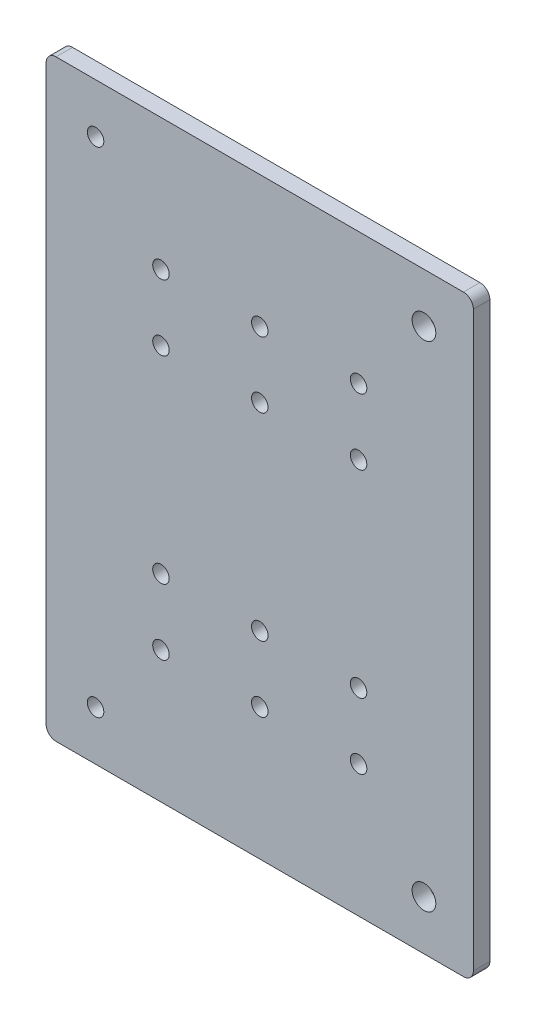
SolidWorks part; units mm, degrees
ref_plane "Płaszczyzna przednia" through (0, 0, 0) normal (0, 0, 1) x (1, 0, 0)
ref_plane "Płaszczyzna górna" through (0, 0, 0) normal (0, 1, 0) x (1, 0, 0)
ref_plane "Płaszczyzna prawa" through (0, 0, 0) normal (1, 0, 0) x (0, 0, -1)
sketch "Sketch1" plane through (0, 0, 0) normal (0, 0, 1) x (1, 0, 0)
  line L0 (64.85, -11.9796) -> (64.85, 60) construction
  line L1 (0, 0) -> (129.7, 0)
  line L2 (0, 0) -> (0, 180)
  line L3 (0, 180) -> (129.7, 180)
  line L4 (129.7, 0) -> (129.7, 180)
  line L5 (-13.2189, 90) -> (166.9359, 90) construction
  line L6 (166.9359, 130) -> (-13.2189, 130) construction
  line L7 (166.9359, 50) -> (-17.016, 50) construction
  line L8 (-17.016, 140) -> (166.9359, 140) construction
  line L9 (-13.2189, 40) -> (174.7412, 40) construction
  line L10 (147.3061, 120) -> (-6.995, 120) construction
  line L11 (140.3481, 60) -> (-6.995, 60) construction
  circle A0 centre (15, 15) radius 2.5
  circle A1 centre (15, 165) radius 2.5
  circle A2 centre (114.7, 165) radius 3.6
  circle A3 centre (114.7, 15) radius 3.6
  circle A4 centre (34.85, 140) radius 2.5
  circle A5 centre (64.85, 140) radius 2.5
  circle A6 centre (94.85, 140) radius 2.5
  circle A7 centre (34.85, 40) radius 2.5
  circle A8 centre (64.85, 40) radius 2.5
  circle A9 centre (94.85, 40) radius 2.5
  circle A10 centre (94.85, 120) radius 2.5
  circle A11 centre (64.85, 120) radius 2.5
  circle A12 centre (34.85, 120) radius 2.5
  circle A13 centre (34.85, 60) radius 2.5
  circle A14 centre (64.85, 60) radius 2.5
  circle A15 centre (94.85, 60) radius 2.5
  point P6 (0, 0)
  point P18 (64.85, 0)
  point P38 (0, 90)
  point P55 (0, 0)
  point P56 (0, 0)
  point P57 (94.85, 120)
  point P58 (94.85, 60)
  point P59 (64.85, 60)
  point P60 (34.85, 60)
  point P61 (64.85, 60.8772)
  point P62 (0, 0)
  point P63 (0, 0)
  point P64 (0, 0)
  dimension "D1" = 5
  dimension "D2" = 5
  dimension "D3" = 7.2
  dimension "D4" = 7.2
  dimension "D19" = 5
  dimension "D5" = 99.7
  dimension "D6" = 150
  dimension "D7" = 15
  dimension "D8" = 15
  dimension "D9" = 15
  dimension "D10" = 30
  dimension "D11" = 40
  dimension "D12" = 40
  dimension "D13" = 10
  dimension "D14" = 10
  dimension "D15" = 30
  dimension "D16" = 30
  dimension "D17" = 30
  dimension "D18" = 30
  dimension "D20" = 30
extrude "Boss-Extrude1" add sketch "Sketch1" along normal blind 5
fillet "Fillet1" radius 3 4 edges at (0, 0, 2.5) (129.7, 0, 2.5) (0, 180, 2.5) (129.7, 180, 2.5)
